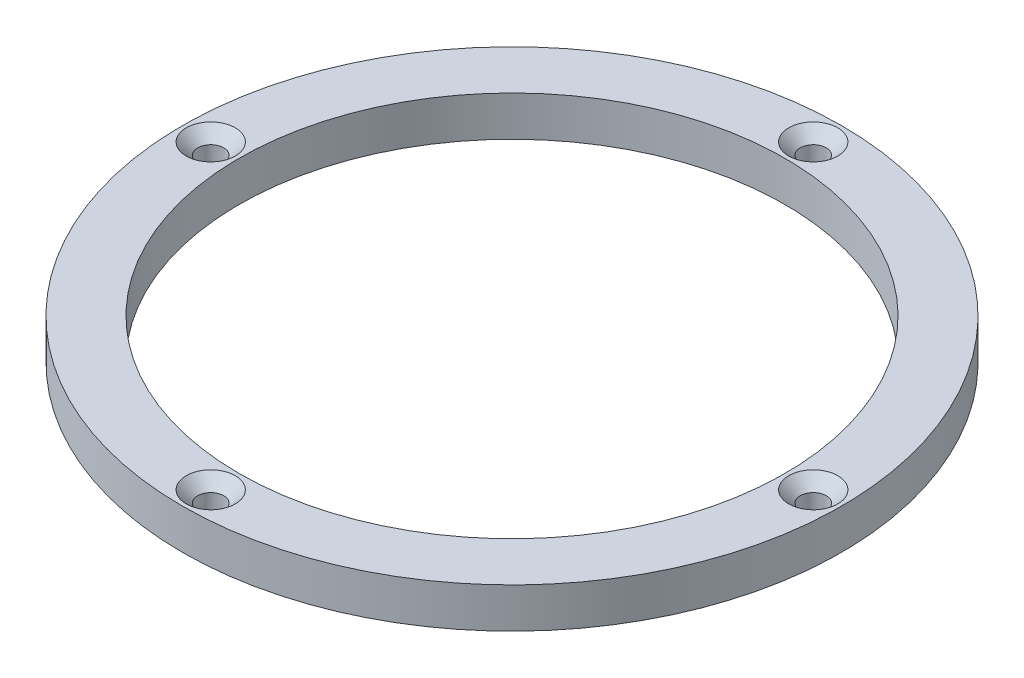
SolidWorks part; units mm, degrees
ref_plane "Front Plane" through (0, 0, 0) normal (0, 0, 1) x (1, 0, 0)
ref_plane "Top Plane" through (0, 0, 0) normal (0, 1, 0) x (1, 0, 0)
ref_plane "Right Plane" through (0, 0, 0) normal (1, 0, 0) x (0, 0, -1)
sketch "Sketch1" plane through (0, 0, 0) normal (0, 1, 0) x (1, 0, 0)
  circle A0 centre (0, 0) radius 69.9
  circle A1 centre (0, 0) radius 57.9
  circle A2 centre (0, 0) radius 63.9 construction
  dimension "D1" = 139.8
  dimension "D2" = 12
  dimension "D3" = 6
extrude "Boss-Extrude1" add sketch "Sketch1" along normal blind 8.5
hole_wizard "CSK for M5 Flat Head Machine Screw1" positions "Sketch4" profile "Sketch3" countersink size "M5" standard "ANSI Metric"
sketch "Sketch4" plane through (0, 8.5, 0) normal (0, 1, 0) x (1, 0, 0)
  circle A0 centre (0, 0) radius 63.9 construction
  point P0 (0, 63.9)
  point P4 (63.9, 0)
  point P6 (0, -63.9)
  point P8 (-63.9, 0)
sketch "Sketch3" plane through (0, 8.5, -63.9) normal (1, 0, 0) x (0, 0, 1)
  line L0 (0, 0) -> (0, 31.6524)
  line L1 (0, 31.6524) -> (2.75, 30)
  line L2 (2.75, 30) -> (2.75, 2.45)
  line L3 (2.75, 2.45) -> (5.2, 0)
  line L5 (5.2, 0) -> (0, 0)
  line L6 (-2.75, 2.45) -> (-5.2, 0) construction
  line L10 (0, 31.6524) -> (-2.75, 30) construction
  line L11 (0, -6.35) -> (0, 107.95) construction
  dimension "Hole Dia." = 5.5
  dimension "Hole Depth" = 30
  dimension "Near C'Sink Dia." = 10.4
  dimension "Near C'Sink Angle" = 90
  dimension "Drill Angle" = 118
